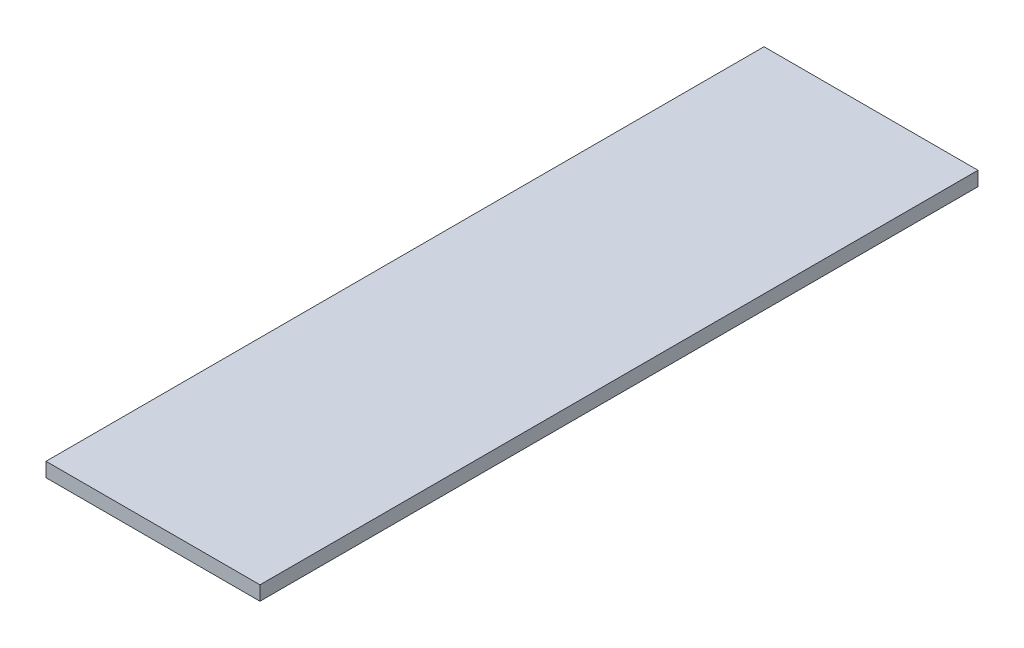
SolidWorks part; units mm, degrees
material "Plain Carbon Steel"
ref_plane "Front Plane" through (0, 0, 0) normal (0, 0, 1) x (1, 0, 0)
ref_plane "Top Plane" through (0, 0, 0) normal (0, 1, 0) x (1, 0, 0)
ref_plane "Right Plane" through (0, 0, 0) normal (1, 0, 0) x (0, 0, -1)
sketch "Sketch1" plane through (0, 0, 0) normal (1, 0, 0) x (0, 0, -1)
  line L1 (-755, -15) -> (755, -15)
  line L2 (-755, -15) -> (-755, 15)
  line L3 (-755, 15) -> (755, 15)
  line L4 (755, -15) -> (755, 15)
  line L5 (-755, -15) -> (755, 15) construction
  line L6 (-755, 15) -> (755, -15) construction
  point P0 (0, 0)
  dimension "D1" = 1510
  dimension "D2" = 30
extrude "Boss-Extrude1" add sketch "Sketch1" along normal mid plane 450
